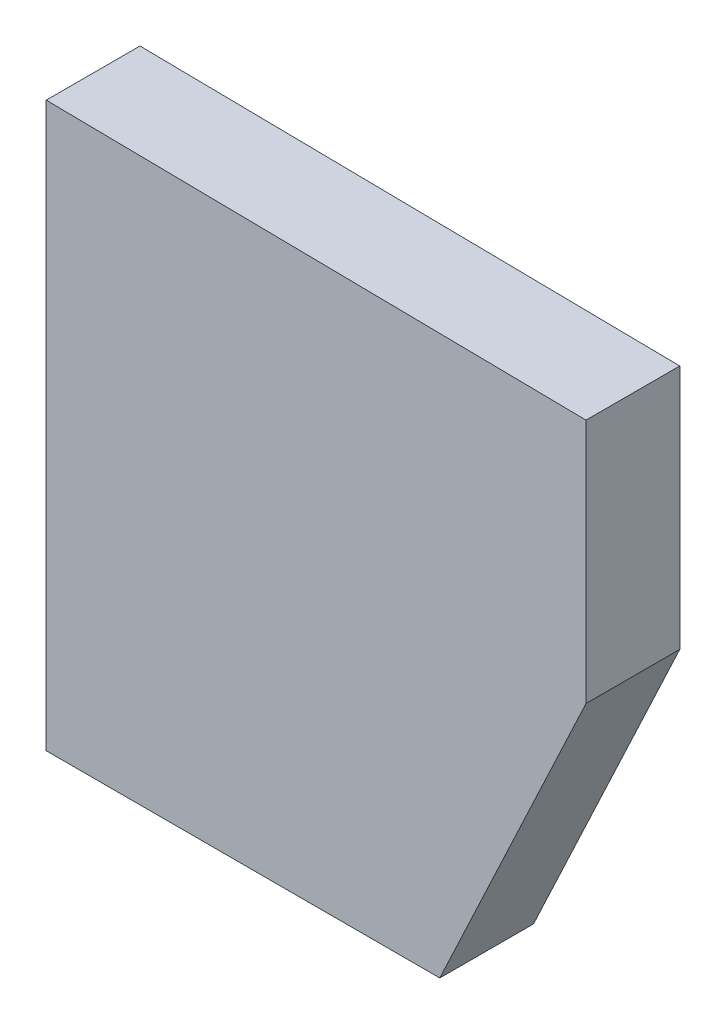
SolidWorks part; units mm, degrees
ref_plane "Plan de face" through (0, 0, 0) normal (0, 0, 1) x (1, 0, 0)
ref_plane "Plan de dessus" through (0, 0, 0) normal (0, 1, 0) x (1, 0, 0)
ref_plane "Plan de droite" through (0, 0, 0) normal (1, 0, 0) x (0, 0, -1)
sketch "Sketch1" plane through (0, 0, 0) normal (0, 0, 1) x (1, 0, 0)
  line L0 (0, 0) -> (91, -1.2182)
  line L2 (66, -95.1482) -> (0, -95.1482)
  line L3 (0, 0) -> (0, -42)
  line L5 (0, -42) -> (210.7454, -42) construction
  line L6 (0, -95.1482) -> (0, -42)
  line L7 (66, -95.1482) -> (91, -42)
  line L8 (91, -42) -> (91, -1.2182)
  dimension "D1" = 91
  dimension "D2" = 97.2
  dimension "D3" = 66
  dimension "D4" = 42
extrude "Boss-Extrude1" add sketch "Sketch1" along normal blind 3
sketch "Sketch2" plane through (0, 0, 3) normal (0, 0, 1) x (1, 0, 0)
  line L5 (0, 0) -> (0, -95.1482)
  line L6 (66, -95.1482) -> (91, -42)
  line L7 (0, -95.1482) -> (66, -95.1482)
  line L8 (66, -95.1482) -> (91, -42)
  line L9 (91, -1.2182) -> (0, 0)
  line L10 (0, 0) -> (0, -95.1482)
  line L12 (0, -95.1482) -> (66, -95.1482)
  line L14 (91, -1.2182) -> (0, 0)
  line L15 (-2, -97.1482) -> (67.2694, -97.1482)
  line L16 (67.2694, -97.1482) -> (93, -42.4469)
  line L17 (93, -42.4469) -> (93, 0.7552)
  line L18 (93, 0.7552) -> (-2, 2.027)
  line L19 (-2, 2.027) -> (-2, -97.1482)
  line L22 (91, -42) -> (91, -1.2182)
  line L23 (91, -42) -> (91, -1.2182)
  dimension "D1" = 0
  dimension "D2" = 2
extrude "Boss-Extrude2" add sketch "Sketch2" against normal blind 16.5
